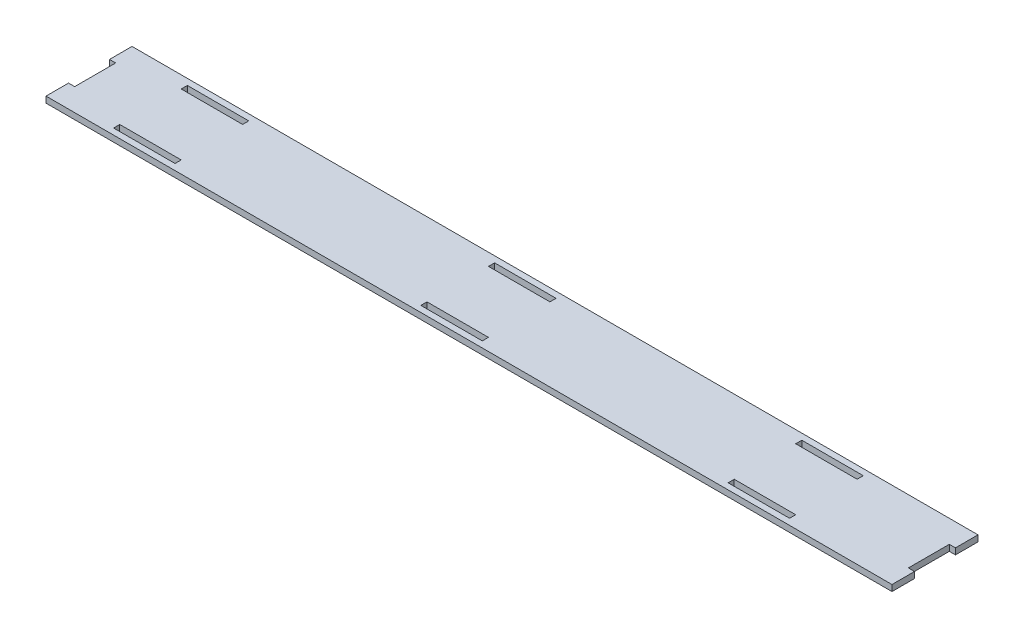
SolidWorks part; units mm, degrees
material "ABS"
ref_plane "Front Plane" through (0, 0, 0) normal (0, 0, 1) x (1, 0, 0)
ref_plane "Top Plane" through (0, 0, 0) normal (0, 1, 0) x (1, 0, 0)
ref_plane "Right Plane" through (0, 0, 0) normal (1, 0, 0) x (0, 0, -1)
sketch "Sketch1" plane through (0, 0, 0) normal (0, 1, 0) x (1, 0, 0)
  line L0 (0, 21) -> (215.87, 21) construction
  line L1 (0, 0) -> (413, 0)
  line L2 (0, 0) -> (0, 11)
  line L3 (0, 42) -> (413, 42)
  line L4 (413, 0) -> (413, 11)
  line L5 (413, 31) -> (410, 31)
  line L7 (413, 11) -> (410, 11)
  line L8 (410, 31) -> (410, 11)
  line L9 (30, 39) -> (60, 39)
  line L10 (30, 39) -> (30, 36)
  line L11 (30, 36) -> (60, 36)
  line L12 (60, 39) -> (60, 36)
  line L13 (180, 39) -> (210, 39)
  line L14 (180, 39) -> (180, 36)
  line L15 (180, 36) -> (210, 36)
  line L16 (210, 39) -> (210, 36)
  line L17 (330, 39) -> (360, 39)
  line L18 (330, 39) -> (330, 36)
  line L19 (330, 36) -> (360, 36)
  line L20 (360, 39) -> (360, 36)
  line L21 (330, 3) -> (330, 6)
  line L22 (360, 3) -> (360, 6)
  line L23 (330, 6) -> (360, 6)
  line L24 (330, 3) -> (360, 3)
  line L25 (210, 3) -> (210, 6)
  line L26 (180, 3) -> (180, 6)
  line L27 (180, 6) -> (210, 6)
  line L28 (180, 3) -> (210, 3)
  line L29 (60, 3) -> (60, 6)
  line L30 (30, 6) -> (60, 6)
  line L31 (30, 3) -> (30, 6)
  line L32 (30, 3) -> (60, 3)
  line L33 (413, 31) -> (413, 42)
  line L34 (0, 31) -> (0, 42)
  line L35 (0, 31) -> (3, 31)
  line L37 (0, 11) -> (3, 11)
  line L38 (3, 31) -> (3, 11)
  point P21 (210, 37.5)
  point P40 (0, 21)
  point P41 (0, 21)
  point P42 (6.1683, 0)
  point P43 (0, 21)
  dimension "D1" = 413
  dimension "D2" = 42
  dimension "D3" = 3
  dimension "D4" = 20
  dimension "D5" = 11
  dimension "D6" = 3
  dimension "D7" = 3
  dimension "D8" = 3
  dimension "D9" = 30
  dimension "D10" = 30
  dimension "D11" = 30
  dimension "D12" = 3
  dimension "D13" = 3
  dimension "D14" = 3
  dimension "D15" = 120
  dimension "D16" = 120
  dimension "D17" = 30
  dimension "D18" = 20
  dimension "D19" = 11
extrude "Boss-Extrude1" add sketch "Sketch1" along normal blind 3
